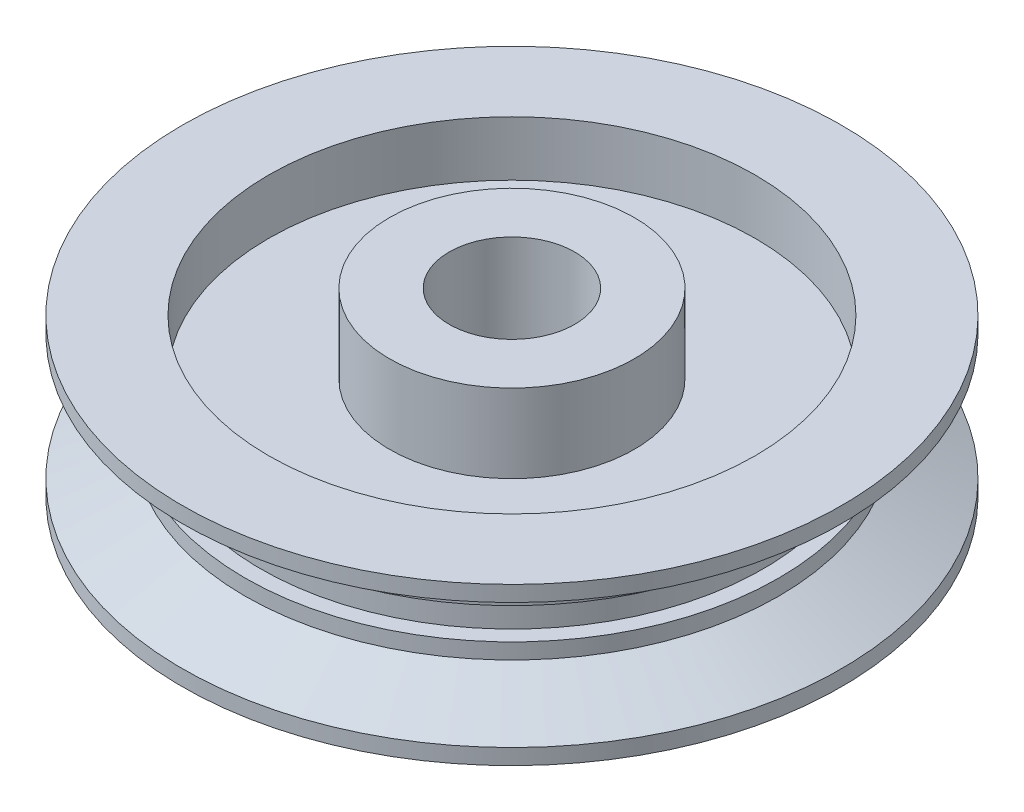
SolidWorks part; units mm, degrees
ref_plane "前视基准面" through (0, 0, 0) normal (0, 0, 1) x (1, 0, 0)
ref_plane "上视基准面" through (0, 0, 0) normal (0, 1, 0) x (1, 0, 0)
ref_plane "右视基准面" through (0, 0, 0) normal (1, 0, 0) x (0, 0, -1)
sketch "草图1" plane through (0, 0, 0) normal (0, 0, 1) x (1, 0, 0)
  line L0 (0, 0) -> (-8, 0)
  line L1 (-8, 0) -> (-8, 0.5)
  line L2 (-8, 0.5) -> (-8.5, 0.5)
  line L3 (-8.5, 0.5) -> (-8.5, 1)
  line L4 (-8.5, 1) -> (-10.5, 2)
  line L5 (-10.5, 2) -> (-10.5, 2.5)
  line L6 (-10.5, 2.5) -> (0, 2.5)
  line L7 (0, 2.5) -> (0, 0)
  dimension "D1" = 8
  dimension "D2" = 0.5
  dimension "D3" = 0.5
  dimension "D4" = 0.5
  dimension "D5" = 10.5
  dimension "D6" = 2.5
  dimension "D7" = 0.5
revolve "旋转1" add sketch "草图1" angle 360 about L7
mirror "镜向1" about plane through (0, 0, 0) normal (0, 1, 0) of "旋转1"
sketch "草图2" plane through (0, 2.5, 0) normal (0, 1, 0) x (1, 0, 0)
  circle A0 centre (0, 0) radius 7.75
  dimension "D1" = 15.5
extrude "切除-拉伸1" cut sketch "草图2" against normal blind 1.75
sketch "草图3" plane through (0, 0.75, 0) normal (0, 1, 0) x (1, 0, 0)
  circle A0 centre (0, 0) radius 3.9
  dimension "D1" = 7.8
extrude "凸台-拉伸1" add sketch "草图3" along normal blind 2.5
mirror "镜向2" about plane through (0, 0, 0) normal (0, 1, 0) of "凸台-拉伸1", "切除-拉伸1"
sketch "草图4" plane through (0, 3.25, 0) normal (0, 1, 0) x (1, 0, 0)
  circle A0 centre (0, 0) radius 2
  dimension "D1" = 4
extrude "切除-拉伸2" cut sketch "草图4" against normal up to next
